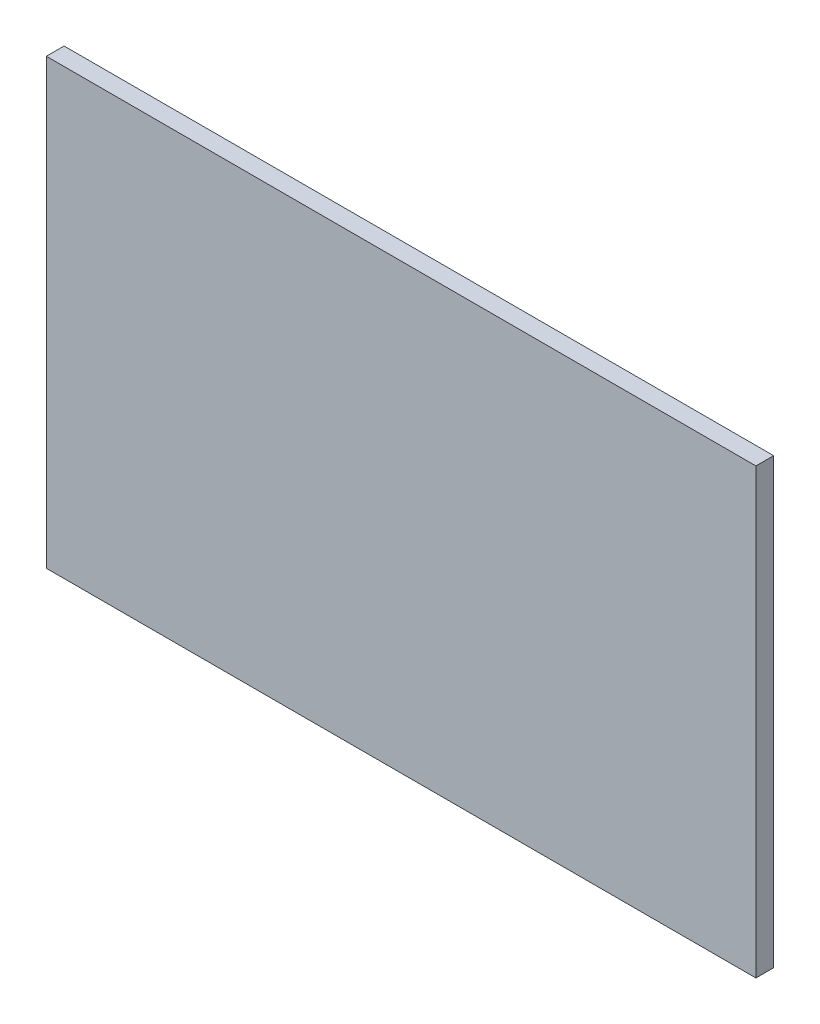
SolidWorks part; units mm, degrees
ref_plane "Plano frontal" through (0, 0, 0) normal (0, 0, 1) x (1, 0, 0)
ref_plane "Plano superior" through (0, 0, 0) normal (0, 1, 0) x (1, 0, 0)
ref_plane "Plano direito" through (0, 0, 0) normal (1, 0, 0) x (0, 0, -1)
sketch "Esboço1" plane through (0, 0, 0) normal (0, 0, 1) x (1, 0, 0)
  line L1 (400, -250) -> (-400, -250)
  line L2 (400, -250) -> (400, 250)
  line L3 (400, 250) -> (-400, 250)
  line L4 (-400, -250) -> (-400, 250)
  line L5 (400, -250) -> (-400, 250) construction
  line L6 (400, 250) -> (-400, -250) construction
  point P0 (0, 0)
  dimension "D1" = 500
  dimension "D2" = 800
extrude "Ressalto-extrusão1" add sketch "Esboço1" along normal blind 20
